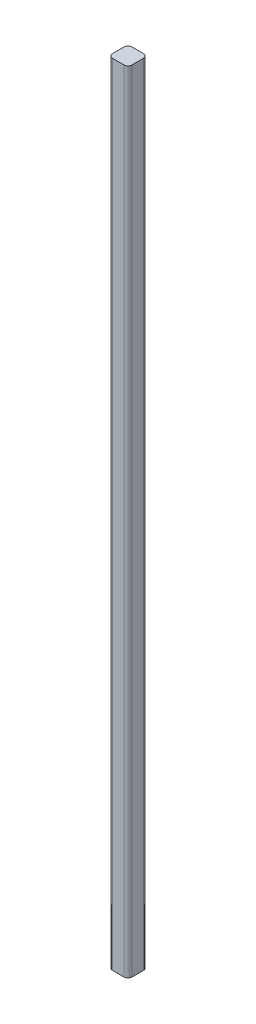
SolidWorks part; units mm, degrees
ref_plane "Plano frontal" through (0, 0, 0) normal (0, 0, 1) x (1, 0, 0)
ref_plane "Plano superior" through (0, 0, 0) normal (0, 1, 0) x (1, 0, 0)
ref_plane "Plano direito" through (0, 0, 0) normal (1, 0, 0) x (0, 0, -1)
sketch "Esboço1" plane through (0, 0, 0) normal (0, 1, 0) x (1, 0, 0)
  line L1 (-3, -5) -> (3, -5)
  line L2 (-5, -3) -> (-5, 3)
  line L3 (-3, 5) -> (3, 5)
  line L4 (5, -3) -> (5, 3)
  line L5 (-5, -5) -> (5, 5) construction
  line L6 (-5, 5) -> (5, -5) construction
  arc A0 (3, 5) -> (5, 3) centre (3, 3) cw
  arc A1 (5, -3) -> (3, -5) centre (3, -3) cw
  arc A2 (-3, -5) -> (-5, -3) centre (-3, -3) cw
  arc A3 (-5, 3) -> (-3, 5) centre (-3, 3) cw
  point P0 (0, 0)
  dimension "D3" = 2
  dimension "D1" = 10
  dimension "D2" = 10
extrude "Ressalto-extrusão1" add sketch "Esboço1" along normal blind 405
